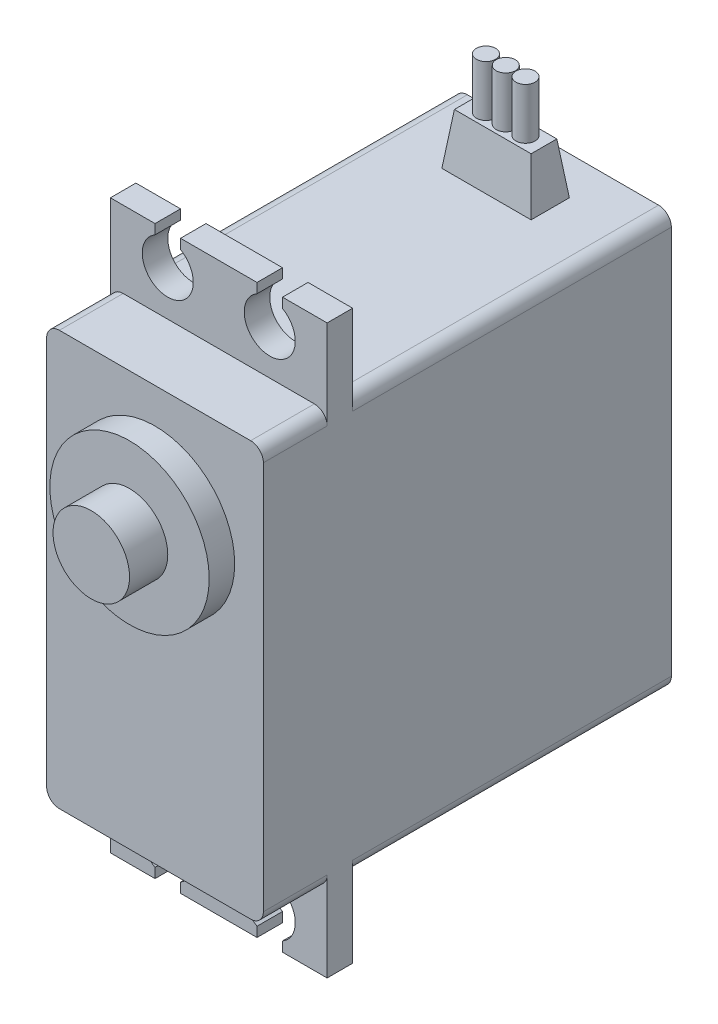
SolidWorks part; units mm, degrees
ref_plane "Front Plane" through (0, 0, 0) normal (1, 0, 0) x (0, 1, 0)
ref_plane "Top Plane" through (0, 0, 0) normal (0, 0, 1) x (0, 1, 0)
ref_plane "Right Plane" through (0, 0, 0) normal (0, 1, 0) x (-1, 0, 0)
sketch "Sketch1" plane through (0, 0, 0) normal (0, 0, 1) x (0, 1, 0)
  line L1 (-16.25, 8.5) -> (16.25, 8.5)
  line L2 (-16.25, 8.5) -> (-16.25, -8.5)
  line L3 (-16.25, -8.5) -> (16.25, -8.5)
  line L4 (16.25, 8.5) -> (16.25, -8.5)
  line L5 (-16.25, 8.5) -> (16.25, -8.5) construction
  line L6 (-16.25, -8.5) -> (16.25, 8.5) construction
  point P0 (0, 0)
  dimension "D1" = 17
  dimension "D2" = 32.5
extrude "Boss-Extrude1" add sketch "Sketch1" along normal blind 32
sketch "Sketch2" plane through (0, 0, 32) normal (0, 0, 1) x (1, 0, 0)
  line L0 (-8.5, 16.25) -> (8.5, 16.25)
  line L1 (8.5, 16.25) -> (8.5, 22.25)
  line L2 (8.5, 22.25) -> (5, 22.25)
  line L3 (5, 22.25) -> (5, 21.4821)
  line L4 (3, 21.4821) -> (3, 22.25)
  line L5 (3, 22.25) -> (-3, 22.25)
  line L6 (0, 0) -> (0, 22.25) construction
  line L7 (-8.5, 16.25) -> (-8.5, 22.25)
  line L8 (-8.5, 22.25) -> (-5, 22.25)
  line L9 (-5, 22.25) -> (-5, 21.4821)
  line L10 (-3, 21.4821) -> (-3, 22.25)
  line L11 (0, 0) -> (50000, 0) construction
  line L12 (8.5, -16.25) -> (8.5, -22.25)
  line L13 (8.5, -22.25) -> (5, -22.25)
  line L14 (5, -22.25) -> (5, -21.4821)
  line L15 (3, -21.4821) -> (3, -22.25)
  line L16 (3, -22.25) -> (-3, -22.25)
  line L17 (-3, -21.4821) -> (-3, -22.25)
  line L18 (-5, -22.25) -> (-5, -21.4821)
  line L19 (-8.5, -22.25) -> (-5, -22.25)
  line L20 (-8.5, -16.25) -> (8.5, -16.25)
  line L21 (-8.5, -16.25) -> (-8.5, -22.25)
  arc A0 (5, 21.4821) -> (3, 21.4821) centre (4, 19.75) cw
  arc A1 (-5, 21.4821) -> (-3, 21.4821) centre (-4, 19.75) ccw
  arc A2 (5, -21.4821) -> (3, -21.4821) centre (4, -19.75) ccw
  arc A3 (-5, -21.4821) -> (-3, -21.4821) centre (-4, -19.75) cw
  dimension "D2" = 2
  dimension "D1" = 2.5
  dimension "D3" = 6
  dimension "D4" = 4
  dimension "D5" = 2
extrude "Boss-Extrude2" add sketch "Sketch2" against normal blind 2 from offset 5 offset against normal yes
sketch "Sketch3" plane through (0, 0, 32) normal (0, 0, 1) x (1, 0, 0)
  line L0 (-8.5, 16.25) -> (8.5, 16.25) construction
  circle A0 centre (0, 7.25) radius 6.25
  dimension "D2" = 12.5
  dimension "D1" = 9
extrude "Boss-Extrude3" add sketch "Sketch3" along normal blind 2
sketch "Sketch4" plane through (0, 0, 34) normal (0, 0, 1) x (1, 0, 0)
  circle A0 centre (0, 7.25) radius 3
  dimension "D1" = 6
extrude "Boss-Extrude4" add sketch "Sketch4" along normal blind 3
sketch "Sketch5" plane through (0, 16.25, 0) normal (0, 1, 0) x (-1, 0, 0)
  line L1 (-3.5, 6) -> (3.5, 6)
  line L2 (-3.5, 6) -> (-3.5, 3)
  line L3 (-3.5, 3) -> (3.5, 3)
  line L4 (3.5, 6) -> (3.5, 3)
  line L5 (-3.5, 6) -> (3.5, 3) construction
  line L6 (-3.5, 3) -> (3.5, 6) construction
  point P0 (0, 4.5)
  dimension "D1" = 3
  dimension "D2" = 3
  dimension "D3" = 7
extrude "Boss-Extrude5" add sketch "Sketch5" along normal blind 4 draft 7
sketch "Sketch6" plane through (0, 20.25, 0) normal (0, 1, 0) x (-1, 0, 0)
  line L0 (3.0089, 3.4911) -> (3.0089, 5.5089) construction
  circle A0 centre (0, 4.4887) radius 0.75
  circle A1 centre (1.55, 4.4887) radius 0.75
  circle A2 centre (-1.55, 4.4887) radius 0.75
  point P11 (3.0089, 4.5)
  dimension "D1" = 1.5
  dimension "D2" = 1.55
  dimension "D3" = 1.55
extrude "Boss-Extrude6" add sketch "Sketch6" along normal blind 4
fillet "Fillet1" radius 1 8 edges at (-8.5, 16.25, 29.5) (-8.5, 16.25, 12.5) (8.5, 16.25, 29.5) (8.5, 16.25, 12.5) (8.5, -16.25, 29.5) (8.5, -16.25, 12.5) (-8.5, -16.25, 12.5) (-8.5, -16.25, 29.5)
